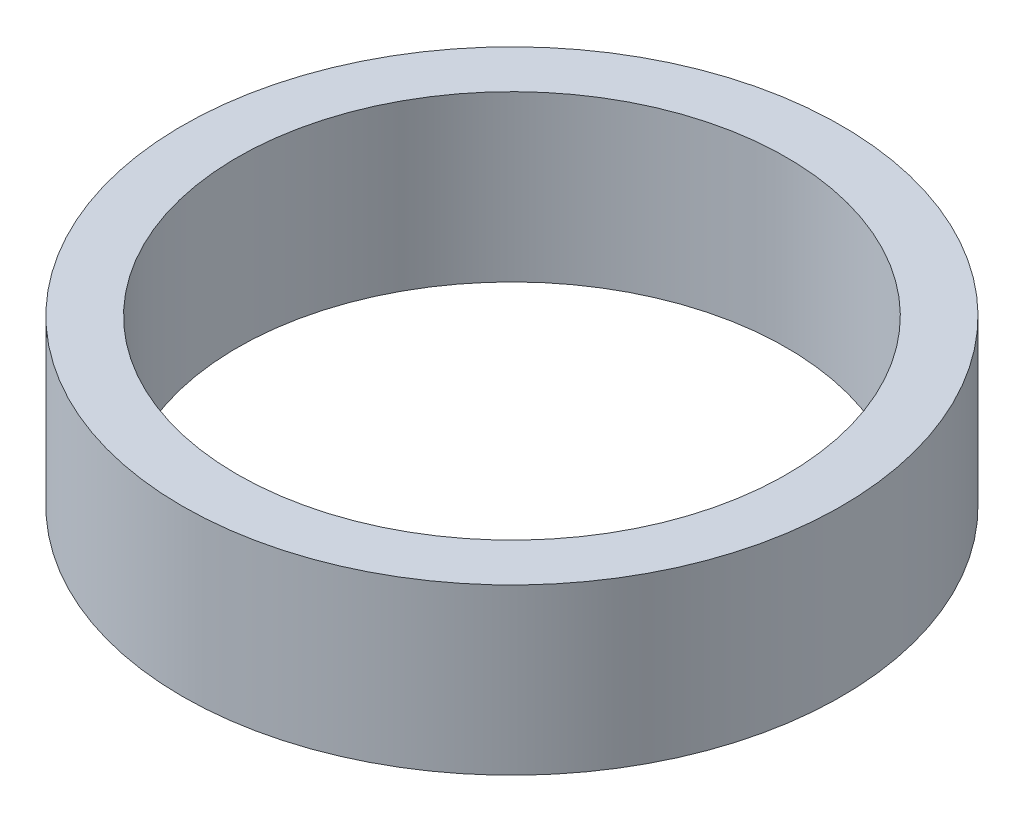
SolidWorks part; units mm, degrees
ref_plane "Front Plane" through (0, 0, 0) normal (0, 0, 1) x (1, 0, 0)
ref_plane "Top Plane" through (0, 0, 0) normal (0, 1, 0) x (1, 0, 0)
ref_plane "Right Plane" through (0, 0, 0) normal (1, 0, 0) x (0, 0, -1)
sketch "Sketch1" plane through (0, 0, 0) normal (0, 1, 0) x (1, 0, 0)
  circle A0 centre (0, 0) radius 30
  circle A1 centre (0, 0) radius 25
  dimension "D1" = 50
  dimension "D2" = 60
extrude "Boss-Extrude1" add sketch "Sketch1" along normal blind 15
equation "\"Outer Diameter\"= 60mm"
equation "\"Inner Diameter\" = 50mm"
equation "\"Bearing Thickness\"= 15mm"
equation "\"D1@Sketch1\"=\"Inner Diameter\""
equation "\"D2@Sketch1\"=\"Outer Diameter\""
equation "\"D1@Boss-Extrude1\"=\"Bearing Thickness\""
